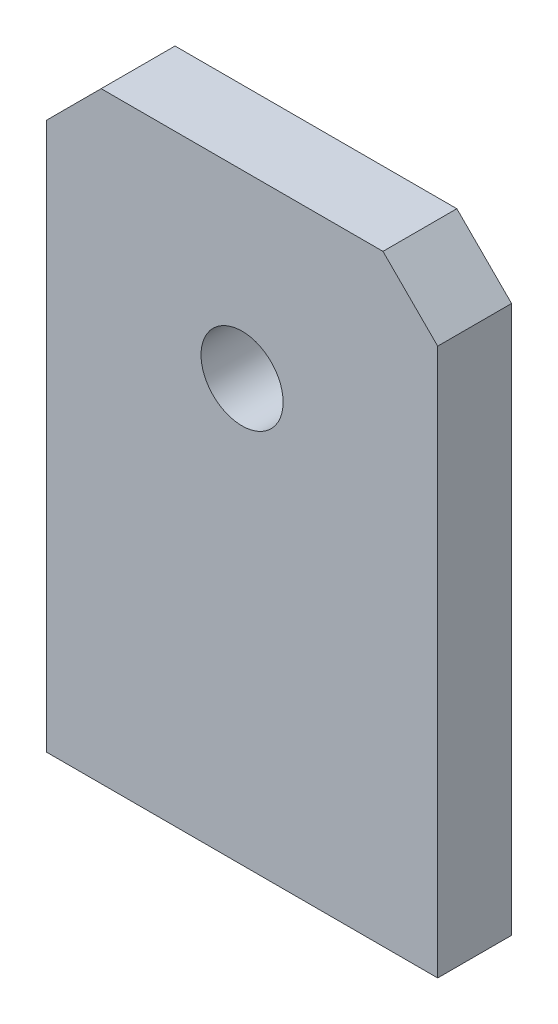
SolidWorks part; units mm, degrees
ref_plane "Front Plane" through (0, 0, 0) normal (0, 0, 1) x (1, 0, 0)
ref_plane "Top Plane" through (0, 0, 0) normal (0, 1, 0) x (1, 0, 0)
ref_plane "Right Plane" through (0, 0, 0) normal (1, 0, 0) x (0, 0, -1)
sketch "Sketch1" plane through (0, 0, 0) normal (0, 0, 1) x (1, 0, 0)
  line L0 (35.75, 77) -> (35.75, 25.4144) construction
  line L1 (0, 0) -> (71.5, 0)
  line L2 (0, 0) -> (0, 110)
  line L3 (0, 110) -> (71.5, 110)
  line L4 (71.5, 0) -> (71.5, 110)
  circle A0 centre (35.75, 77) radius 7.5
  dimension "D3" = 15
  dimension "D1" = 110
  dimension "D2" = 71.5
  dimension "D4" = 77
extrude "Boss-Extrude1" add sketch "Sketch1" along normal blind 13.5
chamfer "Chamfer1" distance 10 angle 45 2 edges at (0, 110, 6.75) (71.5, 110, 6.75)
sketch "Sketch2" plane through (0, 0, 0) normal (0, -1, 0) x (1, 0, 0)
  line L0 (-15.3087, 6.75) -> (91.7438, 6.75) construction
  line L1 (35.75, 28.941) -> (35.75, -14.4297) construction
  line L2 (0, 13.5) -> (0, 0) construction
  line L3 (71.5, 13.5) -> (71.5, 0) construction
  line L4 (0, 13.5) -> (71.5, 13.5) construction
  line L5 (0, 0) -> (71.5, 0) construction
  circle A0 centre (15.75, 6.75) radius 4
  circle A1 centre (55.75, 6.75) radius 4
  dimension "D1" = 8
  dimension "D2" = 8
  dimension "D3" = 40
extrude "Cut-Extrude1" cut sketch "Sketch2" against normal blind 11
